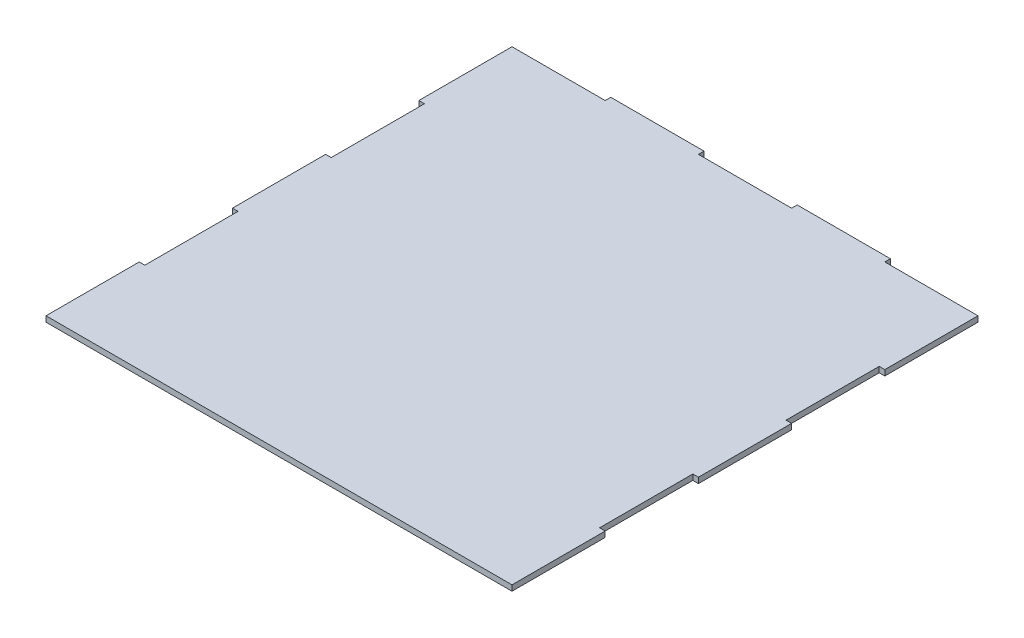
SolidWorks part; units mm, degrees
ref_plane "Front Plane" through (0, 0, 0) normal (0, 0, 1) x (1, 0, 0)
ref_plane "Top Plane" through (0, 0, 0) normal (0, 1, 0) x (1, 0, 0)
ref_plane "Right Plane" through (0, 0, 0) normal (1, 0, 0) x (0, 0, -1)
sketch "Sketch1" plane through (0, 0, 0) normal (0, 1, 0) x (1, 0, 0)
  line L0 (250, 100) -> (250, 150)
  line L1 (0, 0) -> (250, 0)
  line L2 (0, 0) -> (0, 50)
  line L3 (0, 250) -> (50, 250)
  line L4 (250, 0) -> (250, 50)
  line L5 (0, 200) -> (0, 250)
  line L6 (50, 250) -> (50, 253)
  line L7 (50, 253) -> (100, 253)
  line L8 (100, 250) -> (100, 253)
  line L9 (250, 200) -> (247, 200)
  line L10 (200, 250) -> (250, 250)
  line L11 (250, 150) -> (247, 150)
  line L12 (247, 200) -> (247, 150)
  line L17 (0, 200) -> (3, 200)
  line L18 (0, 100) -> (0, 150)
  line L19 (0, 150) -> (3, 150)
  line L20 (3, 200) -> (3, 150)
  line L25 (100, 250) -> (150, 250)
  line L26 (150, 250) -> (150, 253)
  line L27 (150, 253) -> (200, 253)
  line L28 (200, 250) -> (200, 253)
  line L29 (250, 100) -> (247, 100)
  line L30 (250, 200) -> (250, 250)
  line L31 (250, 50) -> (247, 50)
  line L32 (247, 100) -> (247, 50)
  line L33 (0, 100) -> (3, 100)
  line L35 (0, 50) -> (3, 50)
  line L36 (3, 100) -> (3, 50)
  dimension "D1" = 250
  dimension "D2" = 250
  dimension "D3" = 50
  dimension "D4" = 3
  dimension "D5" = 50
  dimension "D6" = 50
  dimension "D7" = 3
  dimension "D8" = 50
  dimension "D9" = 50
  dimension "D10" = 50
extrude "Boss-Extrude1" add sketch "Sketch1" along normal blind 3
equation "\"w\"=3"
equation "\"L\"=50"
